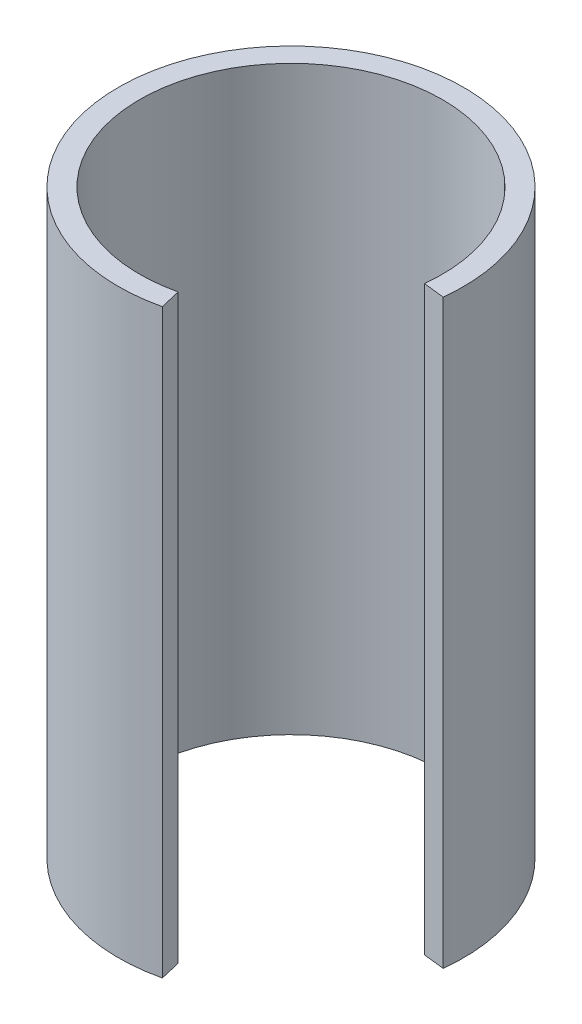
SolidWorks part; units mm, degrees
ref_plane "Front Plane" through (0, 0, 0) normal (0, 0, 1) x (1, 0, 0)
ref_plane "Top Plane" through (0, 0, 0) normal (0, 1, 0) x (1, 0, 0)
ref_plane "Right Plane" through (0, 0, 0) normal (1, 0, 0) x (0, 0, -1)
sketch "Sketch1" plane through (0, 0, 0) normal (0, 1, 0) x (1, 0, 0)
  line L0 (8.9164, -38.0184) -> (38.8039, -4.3771) construction
  line L1 (38.8039, -4.3771) -> (44.2456, -4.9909)
  line L2 (8.9164, -38.0184) -> (10.1668, -43.35)
  line L3 (0, 0) -> (38.8039, -4.3771) construction
  line L4 (0, 0) -> (8.9164, -38.0184) construction
  circle A0 centre (0, 0) radius 39.05 construction
  circle A1 centre (0, 0) radius 44.5262 construction
  arc A2 (38.8039, -4.3771) -> (8.9164, -38.0184) centre (0, 0) ccw
  arc A3 (44.2456, -4.9909) -> (10.1668, -43.35) centre (0, 0) ccw
  dimension "D1" = 45
  dimension "D2" = 70.365
extrude "Boss-Extrude1" add sketch "Sketch1" along normal blind 150
